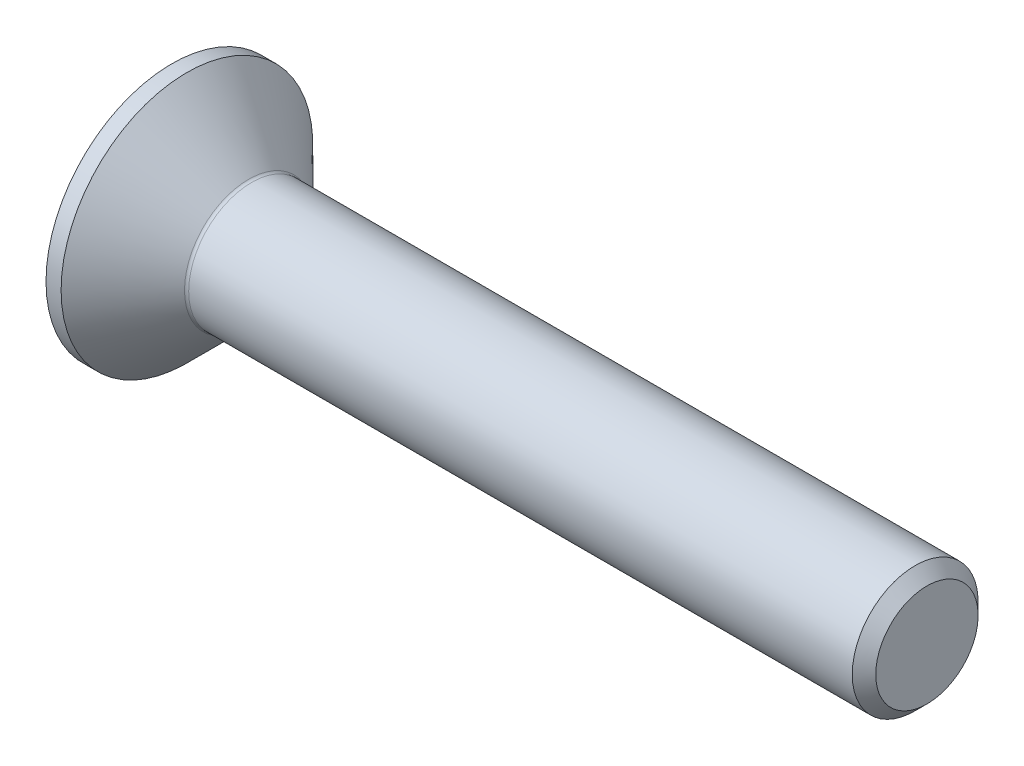
SolidWorks part; units mm, degrees
ref_plane "Plane1" through (0, 0, 0) normal (0, 0, 1) x (1, 0, 0)
ref_plane "Plane2" through (0, 0, 0) normal (0, 1, 0) x (1, 0, 0)
ref_plane "Plane3" through (0, 0, 0) normal (1, 0, 0) x (0, 0, -1)
sketch "BodySke" plane through (0, 0, 0) normal (0, 0, 1) x (1, 0, 0)
  line L0 (0, 0) -> (0, 3)
  line L1 (0.36, 3) -> (1.86, 1.5)
  line L2 (0, 3) -> (0.36, 3)
  line L3 (1.86, 1.5) -> (17.7195, 1.5)
  line L4 (18, 1.2195) -> (18, 0)
  line L5 (18, 0) -> (0, 0)
  line L6 (0, 0) -> (127, 0) construction
  line L7 (0.36, -3) -> (1.86, -1.5) construction
  line L8 (18, 1.2195) -> (17.7195, 1.5)
  line L9 (0, -3) -> (0.36, -3) construction
  line L10 (18, -1.2195) -> (17.7195, -1.5) construction
  line L11 (2.36, 7.85) -> (2.36, -14.375) construction
  line L12 (0, 19.05) -> (0, -3.175) construction
  dimension "D1" = 0.36
  dimension "Diameter" = 3
  dimension "Head_ht" = 1.86
  dimension "Length" = 18
  dimension "Body_ch_ang" = 45
  dimension "Head_dia" = 6
  dimension "Minor_dia" = 2.439
  dimension "Head_ang" = 90
  dimension "Advance" = 0.5
  dimension "Thread_nom" = 18
revolve "BaseBody" add sketch "BodySke" angle 360 about L6
cosmetic thread "ThreadCosmetic" parameters "Thread_length"=15.14, "Thread_minor"=2.439
fillet "Fillet1" radius 0.1 1 edges at (1.86, 0, 1.5)
sketch "Sketch2" plane through (0, 0, 0) normal (0, 0, 1) x (1, 0, 0)
  line L0 (0, 1) -> (1.1, 1)
  line L1 (1.1, 1) -> (1.6774, 0)
  line L2 (0, 0) -> (127, 0) construction
  line L3 (1.6774, 0) -> (0, 0)
  line L4 (0, 0) -> (0, 1)
  line L5 (0, -1) -> (1.1, -1) construction
  line L6 (0, 0) -> (47.625, 0) construction
  line L8 (0, 3) -> (0, -3) construction
  dimension "D2" = 60
  dimension "PreBroach_depth" = 1.1
  dimension "PreBroach_dia" = 2
revolve "PreBroach" cut sketch "Sketch2" angle 360 about L6
sketch "Sketch3" plane through (0, 0, 0) normal (-1, 0, 0) x (0, 0, 1)
  line L0 (-1, -0.5774) -> (-1, 0.5774)
  line L1 (-1, 0.5774) -> (0, 1.1547)
  line L2 (0, 1.1547) -> (1, 0.5774)
  line L3 (1, 0.5774) -> (1, -0.5774)
  line L4 (1, -0.5774) -> (0, -1.1547)
  line L5 (0, -1.1547) -> (-1, -0.5774)
  dimension "D1" = 1
  dimension "D2" = 1
  dimension "D3" = 2
  dimension "Hex_size" = 2
extrude "Hex" cut sketch "Sketch3" against normal blind 1.1
sketch "ThdSchSke" plane through (0, 0, 0) normal (0, 0, 1) x (1, 0, 0)
  line L0 (2.86, -1.2195) -> (2.6636, -1.5)
  line L1 (2.86, -1.2195) -> (3.0564, -1.5)
  line L2 (3.0564, -1.5) -> (3.0564, -1.875)
  line L3 (-3.175, 0) -> (5.1513, 0) construction
  line L4 (0, 3) -> (0, -3) construction
  line L5 (3.0564, -1.875) -> (2.6636, -1.875)
  line L6 (2.6636, -1.875) -> (2.6636, -1.5)
  dimension "Thread_minor" = 2.439
  dimension "Diameter" = 3
  dimension "Start" = 2.86
  dimension "SideAngle" = 55
  dimension "VeeAngle" = 70
  dimension "Overcut" = 3.75
revolve "ThreadSchematic" [suppressed] cut sketch "ThdSchSke" angle 360 about L3
pattern_linear "ThdSchPat" [suppressed]
equation "\"Thread_minor@ThreadCosmetic\"  =  \"Minor_dia@BodySke\""
equation "\"D1@Sketch3\" = \"Hex_size@Sketch3\" / 2"
equation "\"D2@Sketch3\" = \"D1@Sketch3\""
equation "\"D3@Sketch3\" = \"Hex_size@Sketch3\""
equation "\"Thread_length@ThreadCosmetic\" = ((sgn( (\"Length@BodySke\" - \"Advance@BodySke\" * 2.0 - \"Head_ht@BodySke\" ) - \"Thread_nom@BodySke\" )-1)*( (\"Length@BodySke\" - \"Advance@BodySke\" * 2.0 - \"Head_ht@BodySke\" ) - \"Thread_nom@BodySke\" ))/-2+ \"Thread_nom@BodySke\""
equation "\"Thread_minor@ThdSchSke\" = \"Minor_dia@BodySke\""
equation "\"Diameter@ThdSchSke\" = \"Diameter@BodySke\""
equation "\"Overcut@ThdSchSke\" = \"Diameter@BodySke\" * 1.25"
equation "\"Start@ThdSchSke\" = 0.000001 + \"Length@BodySke\" - \"Thread_length@ThreadCosmetic\"  '---Countersunk---"
equation "\"Num_threads@ThdSchPat\" = int( \"Thread_length@ThreadCosmetic\" / \"Advance@BodySke\" + 0.999 )  + 1"
equation "\"Advance@ThdSchPat\" = \"Thread_length@ThreadCosmetic\" /  (\"Num_threads@ThdSchPat\" - 1) 'relax it"
equation "\"Num_threads@ThdSchPat\" = \"Num_threads@ThdSchPat\" - sgn( \"Num_threads@ThdSchPat\" - 1) '---chamfered tips only---"
